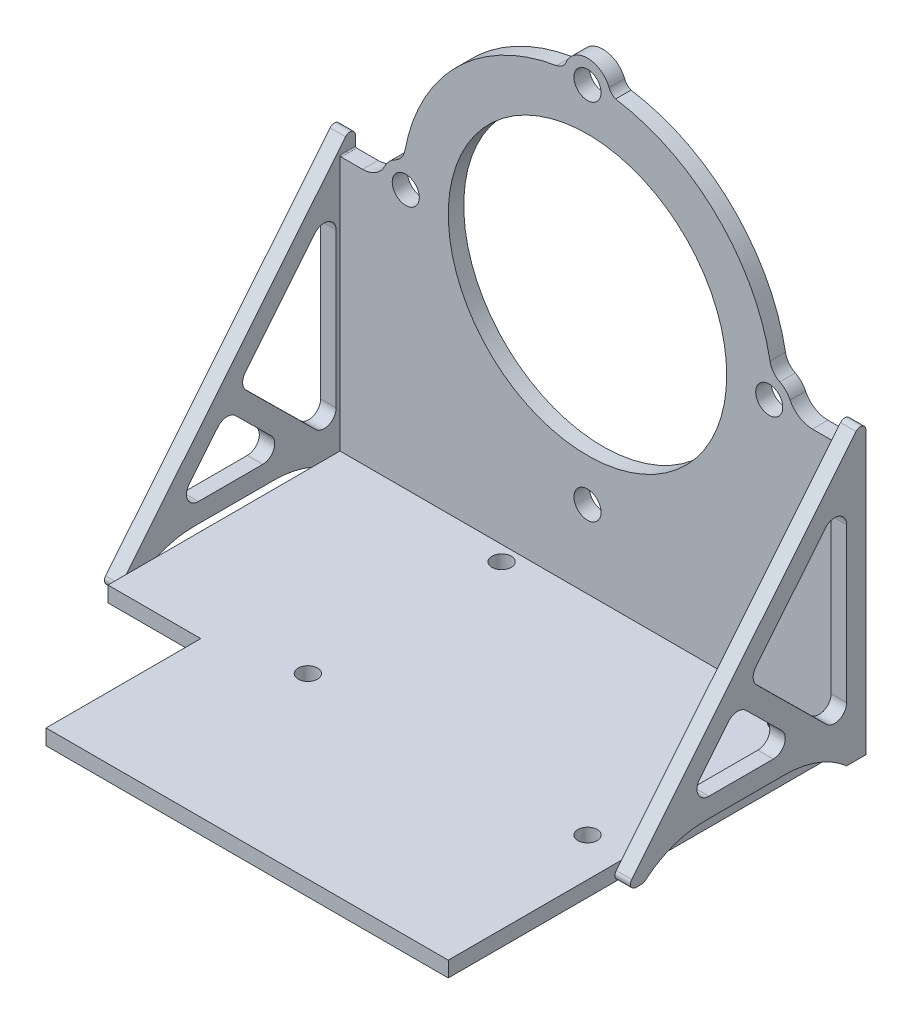
SolidWorks part; units mm, degrees
ref_plane "Front Plane" through (0, 0, 0) normal (0, 0, 1) x (1, 0, 0)
ref_plane "Top Plane" through (0, 0, 0) normal (0, 1, 0) x (1, 0, 0)
ref_plane "Right Plane" through (0, 0, 0) normal (1, 0, 0) x (0, 0, -1)
sketch "Sketch2" plane through (0, 0, 0) normal (0, 1, 0) x (1, 0, 0)
  line L0 (0, 0) -> (0, -101.6)
  line L1 (0, -101.6) -> (38.1, -101.6)
  line L2 (38.1, -101.6) -> (38.1, -165.1)
  line L3 (38.1, -165.1) -> (203.2, -165.1)
  line L4 (203.2, -165.1) -> (203.2, 0)
  line L5 (203.2, 0) -> (0, 0)
  dimension "D1" = 165.1
  dimension "D2" = 165.1
  dimension "D3" = 63.5
  dimension "D4" = 38.1
extrude "Boss-Extrude1" add sketch "Sketch2" along normal blind 6.35
sketch "Sketch3" plane through (0, 0, 0) normal (0, 0, 1) x (1, 0, 0)
  line L0 (203.2, 6.35) -> (203.2, 196.85)
  line L1 (203.2, 196.85) -> (0, 196.85)
  line L2 (0, 196.85) -> (0, 6.35)
  line L3 (0, 6.35) -> (203.2, 6.35)
  dimension "D1" = 190.5
extrude "Boss-Extrude2" add sketch "Sketch3" along normal blind 6.35
sketch "Sketch4" plane through (0, 0, 6.35) normal (0, 0, 1) x (1, 0, 0)
  line L0 (0, 6.35) -> (101.6, 6.35) construction
  line L1 (38.1, 6.35) -> (203.2, 6.35) construction
  line L2 (101.6, 6.35) -> (101.6, 112.7125) construction
  circle A0 centre (101.6, 112.7125) radius 57.15
  dimension "D3" = 114.3
  dimension "D1" = 101.6
  dimension "D2" = 106.3625
extrude "Cut-Extrude1" cut sketch "Sketch4" against normal blind 6.35
sketch "Sketch5" plane through (0, 0, 0) normal (0, 0, -1) x (-1, 0, 0)
  line L0 (0, 6.35) -> (-203.2, 6.35) construction
  line L1 (-101.6, 6.35) -> (-101.6, 38.1125) construction
  circle A0 centre (-101.6, 38.1125) radius 5.5563
  circle A1 centre (-101.6, 112.7125) radius 74.6 construction
  circle A2 centre (-101.6, 187.3125) radius 5.5563
  circle A3 centre (-27, 112.7125) radius 5.5562
  circle A4 centre (-176.2, 112.7125) radius 5.5563
  dimension "D2" = 11.1125
  dimension "D1" = 149.2
extrude "Cut-Extrude2" cut sketch "Sketch5" against normal blind 6.35
sketch "Sketch6" plane through (0, 0, 0) normal (0, 0, -1) x (-1, 0, 0)
  line L0 (-44.45, 112.7125) -> (-25.4, 112.7125) construction
  line L1 (0, 0) -> (0, 111.125) construction
  line L2 (0, 196.85) -> (0, 0) construction
  line L3 (0, 111.125) -> (-203.2, 111.125) construction
  line L4 (-203.2, 196.85) -> (-203.2, 0) construction
  line L5 (0, 111.125) -> (-9.2796, 111.125)
  line L6 (-88.3893, 190.809) -> (-114.449, 190.809) construction
  line L7 (-7.9098, 126.5834) -> (-186.0002, 126.5834) construction
  line L8 (-20.9502, 121.1891) -> (-193.0529, 121.1891) construction
  line L9 (-203.2, 111.125) -> (-193.9204, 111.125)
  line L10 (-203.2, 111.125) -> (-224.6051, 111.125)
  line L11 (-224.6051, 111.125) -> (-224.6051, 212.9952)
  line L12 (-224.6051, 212.9952) -> (24.4438, 212.9952)
  line L13 (24.4438, 212.9952) -> (24.4438, 111.125)
  line L14 (24.4438, 111.125) -> (0, 111.125)
  circle A0 centre (-101.6, 112.7125) radius 76.2 construction
  circle A1 centre (-101.6, 112.7125) radius 57.15 construction
  circle A2 centre (-101.6, 187.3125) radius 9.525 construction
  circle A3 centre (-27, 112.7125) radius 9.525 construction
  circle A4 centre (-176.2, 112.7125) radius 9.525 construction
  arc A5 (-9.2796, 111.125) -> (-18.4256, 116.8605) centre (-9.2796, 121.285) cw
  arc A6 (-18.4256, 116.8605) -> (-22.6558, 121.1891) centre (-27, 112.7125) ccw
  arc A7 (-22.6558, 121.1891) -> (-26.6731, 126.5834) centre (-19.1804, 127.9705) cw
  arc A8 (-26.6731, 126.5834) -> (-88.9376, 187.8531) centre (-101.6, 112.7125) ccw
  arc A9 (-88.9376, 187.8531) -> (-92.74, 190.809) centre (-88.0935, 192.8624) cw
  arc A10 (-92.74, 190.809) -> (-110.46, 190.809) centre (-101.6, 187.3125) ccw
  arc A11 (-110.46, 190.809) -> (-113.1063, 188.0388) centre (-115.1854, 192.6738) cw
  arc A12 (-113.1063, 188.0388) -> (-176.5269, 126.5834) centre (-101.6, 112.7125) ccw
  arc A13 (-176.5269, 126.5834) -> (-180.5442, 121.1891) centre (-184.0196, 127.9705) cw
  arc A14 (-193.9204, 111.125) -> (-184.7744, 116.8605) centre (-193.9204, 121.285) ccw
  arc A15 (-184.7744, 116.8605) -> (-180.5442, 121.1891) centre (-176.2, 112.7125) cw
  dimension "D1" = 19.05
  dimension "D2" = 19.05
  dimension "D7" = 5.08
  dimension "D8" = 2.6463
  dimension "D10" = 10.16
  dimension "D9" = 7.62
  dimension "D11" = 5.08
  dimension "D12" = 7.62
  dimension "D13" = 10.16
  dimension "D3" = 111.125
  dimension "D5" = 249.0489
  dimension "D6" = 21.4051
extrude "Cut-Extrude3" cut sketch "Sketch6" against normal blind 6.35
sketch "Sketch7" plane through (0, 6.35, 0) normal (0, 1, 0) x (1, 0, 0)
  line L0 (203.2, -92.05) -> (187.325, -92.05) construction
  line L1 (203.2, -165.1) -> (203.2, -6.35) construction
  line L2 (0, -6.35) -> (203.2, -6.35) construction
  line L3 (187.325, -92.05) -> (187.325, -6.35) construction
  line L4 (187.325, -12.55) -> (203.2, -12.55) construction
  line L5 (72.525, -12.55) -> (72.525, -92.05) construction
  circle A0 centre (187.325, -92.05) radius 3.9687
  circle A1 centre (187.325, -12.55) radius 3.9687
  circle A2 centre (72.525, -12.55) radius 3.9688
  circle A3 centre (72.525, -92.05) radius 3.9687
  dimension "D3" = 7.9375
  dimension "D1" = 15.875
  dimension "D2" = 85.7
  dimension "D4" = 79.5
  dimension "D5" = 114.8
extrude "Cut-Extrude4" cut sketch "Sketch7" against normal blind 6.35
sketch "Sketch8" plane through (0, 0, 0) normal (1, 0, 0) x (0, 0, -1)
  line L0 (0, 0) -> (-99.2187, 0)
  line L1 (-165.1, 0) -> (0, 0) construction
  line L2 (-99.2187, 0) -> (0, 121.92)
  line L3 (0, 111.125) -> (0, 0) construction
  line L4 (0, 121.92) -> (0, 0)
  dimension "D1" = 121.92
  dimension "D2" = 99.2188
extrude "Boss-Extrude3" add sketch "Sketch8" against normal blind 6.35
sketch "Sketch10" plane through (203.2, 0, 0) normal (1, 0, 0) x (0, 0, -1)
  line L0 (-99.2188, 0) -> (0, 0)
  line L1 (0, 0) -> (0, 121.92)
  line L2 (0, 111.125) -> (0, 0) construction
  line L3 (0, 121.92) -> (-99.2188, 0)
  dimension "D1" = 121.92
  dimension "D2" = 99.2188
extrude "Boss-Extrude4" add sketch "Sketch10" along normal blind 6.35
sketch "Sketch11" plane through (209.55, 0, 0) normal (1, 0, 0) x (0, 0, -1)
  line L1 (-7.9375, 0) -> (-91.2813, 0)
  line L2 (-99.2188, 0) -> (0, 0) construction
  line L3 (-66.0805, 9.525) -> (-33.1383, 9.525)
  arc A0 (-91.2813, 0) -> (-66.0805, 9.525) centre (-66.0805, -28.575) cw
  arc A1 (-33.1383, 9.525) -> (-7.9375, 0) centre (-33.1383, -28.575) cw
  dimension "D4" = 38.1
  dimension "D5" = 38.1
  dimension "D1" = 7.9375
  dimension "D2" = 7.9375
  dimension "D3" = 9.525
extrude "Cut-Extrude5" cut sketch "Sketch11" against normal up to surface (6.35 mm away) contours L1 A0 L3 A1 up to face at (203.2, 3.175, 130.8675)
sketch "Sketch12" plane through (-6.35, 0, 0) normal (-1, 0, 0) x (0, 0, 1)
  line L0 (91.2813, 0) -> (7.9375, 0)
  line L1 (33.1383, 9.525) -> (66.0805, 9.525)
  line L2 (99.2187, 0) -> (0, 0) construction
  arc A0 (7.9375, 0) -> (33.1383, 9.525) centre (33.1383, -28.575) cw
  arc A1 (66.0805, 9.525) -> (91.2813, 0) centre (66.0805, -28.575) cw
  dimension "D1" = 38.1
  dimension "D2" = 38.1
  dimension "D3" = 7.9375
  dimension "D4" = 9.525
  dimension "D5" = 7.9375
extrude "Cut-Extrude6" cut sketch "Sketch12" against normal up to surface (6.35 mm away) up to face at (0, 3.175, 99.1175)
sketch "Sketch13" plane through (209.55, 0, 0) normal (1, 0, 0) x (0, 0, -1)
  line L0 (-7.9375, 99.5912) -> (-7.9375, 10.6912)
  line L1 (0, 0) -> (0, 121.92) construction
  line L2 (-7.9375, 99.5912) -> (-48.0187, 50.3393)
  line L3 (0, 121.92) -> (-99.2188, 0) construction
  line L4 (-48.0187, 50.3393) -> (-7.9375, 10.6912)
  line L5 (-24.1458, 79.6745) -> (-79.515, 11.6368) construction
  line L6 (0, 121.92) -> (-11.0085, 121.92) construction
  line L7 (-89.376, 17.4625) -> (3.2132, 17.4625) construction
  line L8 (-66.0805, 9.525) -> (-33.1383, 9.525) construction
  line L9 (-53.8667, 44.9593) -> (-22.964, 14.3904) construction
  line L10 (-53.0525, 44.1538) -> (-26.0696, 17.4625)
  line L11 (-53.0525, 44.1538) -> (-74.774, 17.4625)
  line L12 (-26.0696, 17.4625) -> (-74.774, 17.4625)
  point P10 (-48.0187, 50.3393)
  point P18 (-7.9375, 10.6912)
  point P21 (-7.9375, 99.5912)
  dimension "D5" = 7.9375
  dimension "D1" = 7.9375
  dimension "D2" = 7.9375
  dimension "D3" = 88.9
  dimension "D4" = 63.5
  dimension "D6" = 7.9375
extrude "Cut-Extrude7" cut sketch "Sketch13" against normal through all contours L11 L12 L10 | L0 L4 L2
fillet "Fillet1" radius 4.92 12 edges at (206.375, 99.5912, 7.9375) (206.375, 17.4625, 26.0696) (206.375, 17.4625, 74.774) (206.375, 44.1538, 53.0525) (206.375, 50.3393, 48.0187) (206.375, 10.6912, 7.9375) (-3.175, 17.4625, 26.0696) (-3.175, 17.4625, 74.774) (-3.175, 44.1538, 53.0525) (-3.175, 50.3393, 48.0187) (-3.175, 10.6912, 7.9375) (-3.175, 99.5912, 7.9375)
fillet "Fillet4" radius 2.286 6 edges at (-3.175, 121.92, 0) (206.375, 121.92, 0) (206.375, 0, 91.2812) (206.375, 0, 99.2187) (-3.175, 0, 91.2813) (-3.175, 0, 99.2187)
fillet "Fillet6" radius 0.508 1 edges at (0, 111.125, 3.175)
